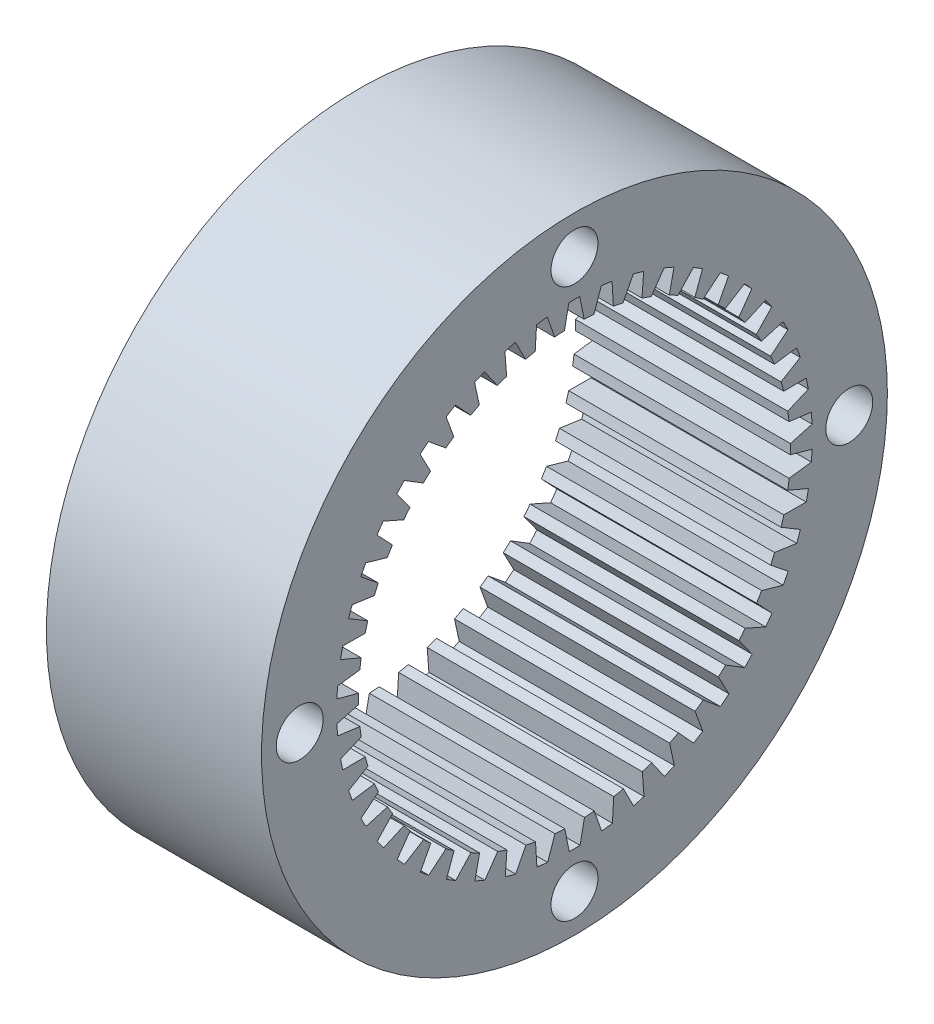
SolidWorks part; units mm, degrees
ref_plane "Plan de face" through (0, 0, 0) normal (0, 0, 1) x (1, 0, 0)
ref_plane "Plan de dessus" through (0, 0, 0) normal (0, 1, 0) x (1, 0, 0)
ref_plane "Plan de droite" through (0, 0, 0) normal (1, 0, 0) x (0, 0, -1)
ref_plane "Plan1" through (0, 0, 0) normal (-1, 0, 0) x (0, -1, 0)
sketch "Esquisse1" plane through (0, 0, 0) normal (-1, 0, 0) x (0, -1, 0)
  line L0 (5.515, -9.569) -> (5.8312, -10.6718)
  line L1 (5.3392, -10.9262) -> (4.6219, -10.0309)
  line L2 (4.1607, -10.2308) -> (4.3238, -11.3664)
  line L3 (3.8017, -11.5515) -> (3.213, -10.5668)
  line L4 (2.7288, -10.7021) -> (2.7358, -11.8493)
  line L5 (2.1933, -11.9616) -> (1.7442, -10.9059)
  line L6 (1.2462, -10.974) -> (1.0968, -12.1114)
  line L7 (0.5441, -12.1488) -> (0.243, -11.0418)
  line L8 (-0.2597, -11.0414) -> (-0.5626, -12.148)
  line L9 (-1.1152, -12.1098) -> (-1.2628, -10.9721)
  line L10 (-1.7608, -10.9032) -> (-2.2115, -11.9582)
  line L11 (-2.7537, -11.8451) -> (-2.7451, -10.6979)
  line L12 (-3.229, -10.5619) -> (-3.8192, -11.5457)
  line L13 (-4.341, -11.3598) -> (-4.1762, -10.2245)
  line L14 (-4.6371, -10.0239) -> (-5.3558, -10.9181)
  line L15 (-5.8474, -10.6629) -> (-5.5296, -9.5606)
  line L16 (-5.9589, -9.2991) -> (-6.7926, -10.0872)
  line L17 (-7.2449, -9.7674) -> (-6.7799, -8.7186)
  line L18 (-7.1696, -8.4011) -> (-8.1028, -9.0683)
  line L19 (-8.5074, -8.6899) -> (-7.9039, -7.7142)
  line L20 (-8.2468, -7.3466) -> (-9.2622, -7.8805)
  line L21 (-9.6114, -7.4505) -> (-8.8807, -6.5661)
  line L22 (-9.1703, -6.1552) -> (-10.249, -6.5459)
  line L23 (-10.5364, -6.0724) -> (-9.6921, -5.2957)
  line L24 (-9.923, -4.8492) -> (-11.0448, -5.0894)
  line L25 (-11.2651, -4.5811) -> (-10.3229, -3.9266)
  line L26 (-10.4909, -3.4528) -> (-11.635, -3.538)
  line L27 (-11.784, -3.0045) -> (-10.7614, -2.4844)
  line L28 (-10.8633, -1.9922) -> (-12.0084, -1.9208)
  line L29 (-12.0834, -1.3719) -> (-10.9995, -0.9959)
  line L30 (-11.0334, -0.4944) -> (-12.1581, -0.2677)
  line L31 (-12.1576, 0.2862) -> (-11.0327, 0.5111)
  line L32 (-10.998, 1.0126) -> (-12.0813, 1.3903)
  line L33 (-12.0054, 1.939) -> (-10.8603, 2.0086)
  line L34 (-10.7577, 2.5007) -> (-11.7794, 3.0224)
  line L35 (-11.6296, 3.5557) -> (-10.4856, 3.4687)
  line L36 (-10.3169, 3.9423) -> (-11.2582, 4.5982)
  line L37 (-11.0371, 5.1061) -> (-9.9157, 4.8642)
  line L38 (-9.684, 5.3104) -> (-10.5272, 6.0884)
  line L39 (-10.239, 6.5614) -> (-9.161, 6.1691)
  line L40 (-8.8707, 6.5796) -> (-9.6001, 7.4651)
  line L41 (-9.2502, 7.8945) -> (-8.2356, 7.3591)
  line L42 (-7.8922, 7.7262) -> (-8.4942, 8.7028)
  line L43 (-8.0891, 9.0806) -> (-7.1568, 8.4119)
  line L44 (-6.7666, 8.7289) -> (-7.23, 9.7784)
  line L45 (-6.7773, 10.0975) -> (-5.9448, 9.3081)
  line L46 (-5.515, 9.569) -> (-5.8312, 10.6718)
  line L47 (-5.3392, 10.9262) -> (-4.6219, 10.0309)
  line L48 (-4.1607, 10.2308) -> (-4.3238, 11.3664)
  line L49 (-3.8017, 11.5515) -> (-3.213, 10.5668)
  line L50 (-2.7288, 10.7021) -> (-2.7358, 11.8493)
  line L51 (-2.1933, 11.9616) -> (-1.7442, 10.9059)
  line L52 (-1.2462, 10.974) -> (-1.0968, 12.1114)
  line L53 (-0.5441, 12.1488) -> (-0.243, 11.0418)
  line L54 (0.2597, 11.0414) -> (0.5626, 12.148)
  line L55 (1.1152, 12.1098) -> (1.2628, 10.9721)
  line L56 (1.7608, 10.9032) -> (2.2115, 11.9582)
  line L57 (2.7537, 11.8451) -> (2.7451, 10.6979)
  line L58 (3.229, 10.5619) -> (3.8192, 11.5457)
  line L59 (4.341, 11.3598) -> (4.1762, 10.2245)
  line L60 (4.6371, 10.0239) -> (5.3558, 10.9181)
  line L61 (5.8474, 10.6629) -> (5.5296, 9.5606)
  line L62 (5.9589, 9.2991) -> (6.7926, 10.0872)
  line L63 (7.2449, 9.7674) -> (6.7799, 8.7186)
  line L64 (7.1696, 8.4011) -> (8.1028, 9.0683)
  line L65 (8.5074, 8.6899) -> (7.9039, 7.7142)
  line L66 (8.2468, 7.3466) -> (9.2622, 7.8805)
  line L67 (9.6114, 7.4505) -> (8.8807, 6.5661)
  line L68 (9.1703, 6.1552) -> (10.249, 6.5459)
  line L69 (10.5364, 6.0724) -> (9.6921, 5.2957)
  line L70 (9.923, 4.8492) -> (11.0448, 5.0894)
  line L71 (11.2651, 4.5811) -> (10.3229, 3.9266)
  line L72 (10.4909, 3.4528) -> (11.635, 3.538)
  line L73 (11.784, 3.0045) -> (10.7614, 2.4844)
  line L74 (10.8633, 1.9922) -> (12.0084, 1.9208)
  line L75 (12.0834, 1.3719) -> (10.9995, 0.9959)
  line L76 (11.0334, 0.4944) -> (12.1581, 0.2677)
  line L77 (12.1576, -0.2862) -> (11.0327, -0.5111)
  line L78 (10.998, -1.0126) -> (12.0813, -1.3903)
  line L79 (12.0054, -1.939) -> (10.8603, -2.0086)
  line L80 (10.7577, -2.5007) -> (11.7794, -3.0224)
  line L81 (11.6296, -3.5557) -> (10.4856, -3.4687)
  line L82 (10.3169, -3.9423) -> (11.2582, -4.5982)
  line L83 (11.0371, -5.1061) -> (9.9157, -4.8642)
  line L84 (9.684, -5.3104) -> (10.5272, -6.0884)
  line L85 (10.239, -6.5614) -> (9.161, -6.1691)
  line L86 (8.8707, -6.5796) -> (9.6001, -7.4651)
  line L87 (9.2502, -7.8945) -> (8.2356, -7.3591)
  line L88 (7.8922, -7.7262) -> (8.4942, -8.7028)
  line L89 (8.0891, -9.0806) -> (7.1568, -8.4119)
  line L90 (6.7666, -8.7289) -> (7.23, -9.7784)
  line L91 (6.7773, -10.0975) -> (5.9448, -9.3081)
  circle A0 centre (0, 0) radius 16
  circle A1 centre (0, -14.05) radius 1.2
  circle A2 centre (14.05, 0) radius 1.2
  circle A3 centre (0, 14.05) radius 1.2
  arc A4 (5.9448, -9.3081) -> (5.515, -9.569) centre (0, 0) cw
  arc A5 (5.8312, -10.6718) -> (5.3392, -10.9262) centre (0, 0) cw
  arc A6 (4.6219, -10.0309) -> (4.1607, -10.2308) centre (0, 0) cw
  arc A7 (4.3238, -11.3664) -> (3.8017, -11.5515) centre (0, 0) cw
  arc A8 (3.213, -10.5668) -> (2.7288, -10.7021) centre (0, 0) cw
  arc A9 (2.7358, -11.8493) -> (2.1933, -11.9616) centre (0, 0) cw
  arc A10 (1.7442, -10.9059) -> (1.2462, -10.974) centre (0, 0) cw
  arc A11 (1.0968, -12.1114) -> (0.5441, -12.1488) centre (0, 0) cw
  arc A12 (0.243, -11.0418) -> (-0.2597, -11.0414) centre (0, 0) cw
  arc A13 (-0.5626, -12.148) -> (-1.1152, -12.1098) centre (0, 0) cw
  arc A14 (-1.2628, -10.9721) -> (-1.7608, -10.9032) centre (0, 0) cw
  arc A15 (-2.2115, -11.9582) -> (-2.7537, -11.8451) centre (0, 0) cw
  arc A16 (-2.7451, -10.6979) -> (-3.229, -10.5619) centre (0, 0) cw
  arc A17 (-3.8192, -11.5457) -> (-4.341, -11.3598) centre (0, 0) cw
  arc A18 (-4.1762, -10.2245) -> (-4.6371, -10.0239) centre (0, 0) cw
  arc A19 (-5.3558, -10.9181) -> (-5.8474, -10.6629) centre (0, 0) cw
  arc A20 (-5.5296, -9.5606) -> (-5.9589, -9.2991) centre (0, 0) cw
  arc A21 (-6.7926, -10.0872) -> (-7.2449, -9.7674) centre (0, 0) cw
  arc A22 (-6.7799, -8.7186) -> (-7.1696, -8.4011) centre (0, 0) cw
  arc A23 (-8.1028, -9.0683) -> (-8.5074, -8.6899) centre (0, 0) cw
  arc A24 (-7.9039, -7.7142) -> (-8.2468, -7.3466) centre (0, 0) cw
  arc A25 (-9.2622, -7.8805) -> (-9.6114, -7.4505) centre (0, 0) cw
  arc A26 (-8.8807, -6.5661) -> (-9.1703, -6.1552) centre (0, 0) cw
  arc A27 (-10.249, -6.5459) -> (-10.5364, -6.0724) centre (0, 0) cw
  arc A28 (-9.6921, -5.2957) -> (-9.923, -4.8492) centre (0, 0) cw
  arc A29 (-11.0448, -5.0894) -> (-11.2651, -4.5811) centre (0, 0) cw
  arc A30 (-10.3229, -3.9266) -> (-10.4909, -3.4528) centre (0, 0) cw
  arc A31 (-11.635, -3.538) -> (-11.784, -3.0045) centre (0, 0) cw
  arc A32 (-10.7614, -2.4844) -> (-10.8633, -1.9922) centre (0, 0) cw
  arc A33 (-12.0084, -1.9208) -> (-12.0834, -1.3719) centre (0, 0) cw
  arc A34 (-10.9995, -0.9959) -> (-11.0334, -0.4944) centre (0, 0) cw
  arc A35 (-12.1581, -0.2677) -> (-12.1576, 0.2862) centre (0, 0) cw
  arc A36 (-11.0327, 0.5111) -> (-10.998, 1.0126) centre (0, 0) cw
  arc A37 (-12.0813, 1.3903) -> (-12.0054, 1.939) centre (0, 0) cw
  arc A38 (-10.8603, 2.0086) -> (-10.7577, 2.5007) centre (0, 0) cw
  arc A39 (-11.7794, 3.0224) -> (-11.6296, 3.5557) centre (0, 0) cw
  arc A40 (-10.4856, 3.4687) -> (-10.3169, 3.9423) centre (0, 0) cw
  arc A41 (-11.2582, 4.5982) -> (-11.0371, 5.1061) centre (0, 0) cw
  arc A42 (-9.9157, 4.8642) -> (-9.684, 5.3104) centre (0, 0) cw
  arc A43 (-10.5272, 6.0884) -> (-10.239, 6.5614) centre (0, 0) cw
  arc A44 (-9.161, 6.1691) -> (-8.8707, 6.5796) centre (0, 0) cw
  arc A45 (-9.6001, 7.4651) -> (-9.2502, 7.8945) centre (0, 0) cw
  arc A46 (-8.2356, 7.3591) -> (-7.8922, 7.7262) centre (0, 0) cw
  arc A47 (-8.4942, 8.7028) -> (-8.0891, 9.0806) centre (0, 0) cw
  arc A48 (-7.1568, 8.4119) -> (-6.7666, 8.7289) centre (0, 0) cw
  arc A49 (-7.23, 9.7784) -> (-6.7773, 10.0975) centre (0, 0) cw
  arc A50 (-5.9448, 9.3081) -> (-5.515, 9.569) centre (0, 0) cw
  arc A51 (-5.8312, 10.6718) -> (-5.3392, 10.9262) centre (0, 0) cw
  arc A52 (-4.6219, 10.0309) -> (-4.1607, 10.2308) centre (0, 0) cw
  arc A53 (-4.3238, 11.3664) -> (-3.8017, 11.5515) centre (0, 0) cw
  arc A54 (-3.213, 10.5668) -> (-2.7288, 10.7021) centre (0, 0) cw
  arc A55 (-2.7358, 11.8493) -> (-2.1933, 11.9616) centre (0, 0) cw
  arc A56 (-1.7442, 10.9059) -> (-1.2462, 10.974) centre (0, 0) cw
  arc A57 (-1.0968, 12.1114) -> (-0.5441, 12.1488) centre (0, 0) cw
  arc A58 (-0.243, 11.0418) -> (0.2597, 11.0414) centre (0, 0) cw
  arc A59 (0.5626, 12.148) -> (1.1152, 12.1098) centre (0, 0) cw
  arc A60 (1.2628, 10.9721) -> (1.7608, 10.9032) centre (0, 0) cw
  arc A61 (2.2115, 11.9582) -> (2.7537, 11.8451) centre (0, 0) cw
  arc A62 (2.7451, 10.6979) -> (3.229, 10.5619) centre (0, 0) cw
  arc A63 (3.8192, 11.5457) -> (4.341, 11.3598) centre (0, 0) cw
  arc A64 (4.1762, 10.2245) -> (4.6371, 10.0239) centre (0, 0) cw
  arc A65 (5.3558, 10.9181) -> (5.8474, 10.6629) centre (0, 0) cw
  arc A66 (5.5296, 9.5606) -> (5.9589, 9.2991) centre (0, 0) cw
  arc A67 (6.7926, 10.0872) -> (7.2449, 9.7674) centre (0, 0) cw
  arc A68 (6.7799, 8.7186) -> (7.1696, 8.4011) centre (0, 0) cw
  arc A69 (8.1028, 9.0683) -> (8.5074, 8.6899) centre (0, 0) cw
  arc A70 (7.9039, 7.7142) -> (8.2468, 7.3466) centre (0, 0) cw
  arc A71 (9.2622, 7.8805) -> (9.6114, 7.4505) centre (0, 0) cw
  arc A72 (8.8807, 6.5661) -> (9.1703, 6.1552) centre (0, 0) cw
  arc A73 (10.249, 6.5459) -> (10.5364, 6.0724) centre (0, 0) cw
  arc A74 (9.6921, 5.2957) -> (9.923, 4.8492) centre (0, 0) cw
  arc A75 (11.0448, 5.0894) -> (11.2651, 4.5811) centre (0, 0) cw
  arc A76 (10.3229, 3.9266) -> (10.4909, 3.4528) centre (0, 0) cw
  arc A77 (11.635, 3.538) -> (11.784, 3.0045) centre (0, 0) cw
  arc A78 (10.7614, 2.4844) -> (10.8633, 1.9922) centre (0, 0) cw
  arc A79 (12.0084, 1.9208) -> (12.0834, 1.3719) centre (0, 0) cw
  arc A80 (10.9995, 0.9959) -> (11.0334, 0.4944) centre (0, 0) cw
  arc A81 (12.1581, 0.2677) -> (12.1576, -0.2862) centre (0, 0) cw
  arc A82 (11.0327, -0.5111) -> (10.998, -1.0126) centre (0, 0) cw
  arc A83 (12.0813, -1.3903) -> (12.0054, -1.939) centre (0, 0) cw
  arc A84 (10.8603, -2.0086) -> (10.7577, -2.5007) centre (0, 0) cw
  arc A85 (11.7794, -3.0224) -> (11.6296, -3.5557) centre (0, 0) cw
  arc A86 (10.4856, -3.4687) -> (10.3169, -3.9423) centre (0, 0) cw
  arc A87 (11.2582, -4.5982) -> (11.0371, -5.1061) centre (0, 0) cw
  arc A88 (9.9157, -4.8642) -> (9.684, -5.3104) centre (0, 0) cw
  arc A89 (10.5272, -6.0884) -> (10.239, -6.5614) centre (0, 0) cw
  arc A90 (9.161, -6.1691) -> (8.8707, -6.5796) centre (0, 0) cw
  arc A91 (9.6001, -7.4651) -> (9.2502, -7.8945) centre (0, 0) cw
  arc A92 (8.2356, -7.3591) -> (7.8922, -7.7262) centre (0, 0) cw
  arc A93 (8.4942, -8.7028) -> (8.0891, -9.0806) centre (0, 0) cw
  arc A94 (7.1568, -8.4119) -> (6.7666, -8.7289) centre (0, 0) cw
  arc A95 (7.23, -9.7784) -> (6.7773, -10.0975) centre (0, 0) cw
  circle A96 centre (-14.05, 0) radius 1.2
extrude "Boss.-Extru.1" add sketch "Esquisse1" against normal blind 11
